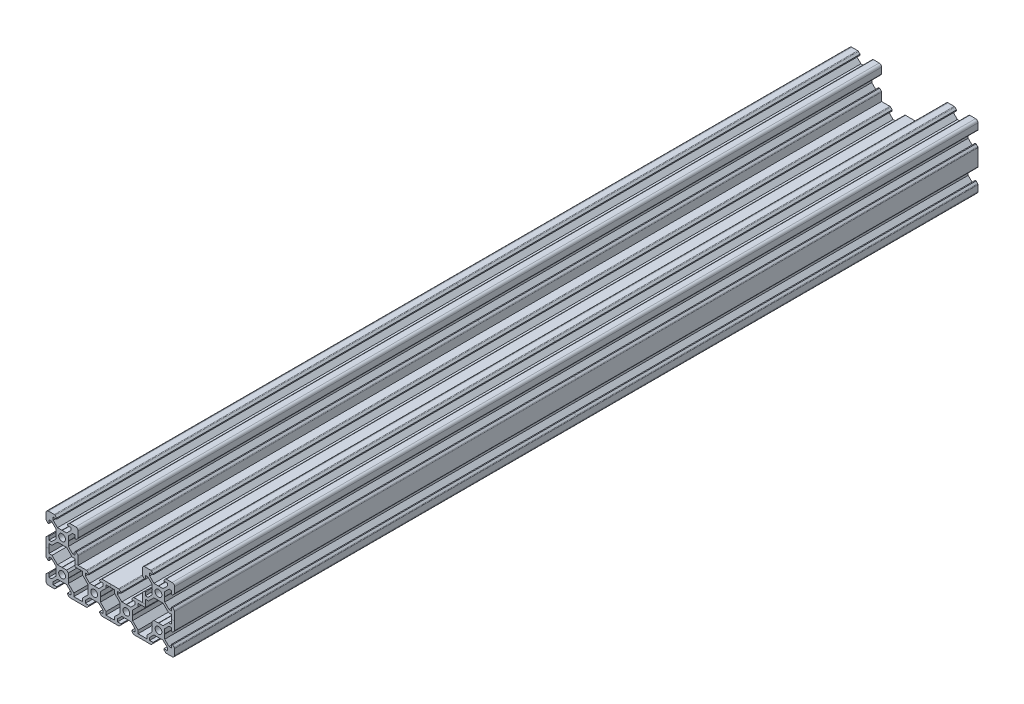
SolidWorks part; units mm, degrees
material "6063-T5"
ref_plane "Front" through (0, 0, 0) normal (0, 0, 1) x (1, 0, 0)
ref_plane "Top" through (0, 0, 0) normal (0, 1, 0) x (1, 0, 0)
ref_plane "Right" through (0, 0, 0) normal (1, 0, 0) x (0, 0, -1)
sketch "Sketch1" plane through (0, 0, 0) normal (0, 0, 1) x (1, 0, 0)
  line L0 (0, 32.3219) -> (0, -50.1713) construction
  line L1 (-2.8395, 3.9) -> (-0.1, 3.9)
  line L2 (-3.9, 2.8395) -> (-3.9, 0.1)
  line L3 (-2.8395, -3.9) -> (-0.1, -3.9)
  line L4 (3.9, 2.8395) -> (3.9, 0.1)
  line L5 (-29.7903, 0) -> (30, 0) construction
  line L6 (-0.1, -3.9) -> (0, -3.8)
  line L7 (-8.5, 10) -> (-4.8658, 10)
  line L8 (-10, 8.5) -> (-10, 4.8627)
  line L9 (-2.8395, -16.1) -> (-6.24, -12.6995)
  line L10 (10, 8.5) -> (10, 4.8627)
  line L11 (0, -3.8) -> (0.1, -3.9)
  line L12 (0.1, -3.9) -> (2.8395, -3.9)
  line L13 (-0.1, 3.9) -> (0, 3.8)
  line L14 (0, 3.8) -> (0.1, 3.9)
  line L15 (10, -10) -> (-10, 10) construction
  line L16 (-10, -10) -> (10, 10) construction
  line L17 (0.1, 3.9) -> (2.8395, 3.9)
  line L18 (-3.9, 0.1) -> (-3.8, 0)
  line L19 (-3.8, 0) -> (-3.9, -0.1)
  line L20 (-3.9, -0.1) -> (-3.9, -2.8395)
  line L21 (3.9, 0.1) -> (3.8, 0)
  line L22 (3.8, 0) -> (3.9, -0.1)
  line L23 (3.9, -0.1) -> (3.9, -2.8395)
  line L24 (0, -20) -> (58.4732, -20) construction
  line L25 (-3.9, 2.8395) -> (-6.561, 5.5005)
  line L26 (30, -50.1713) -> (30, 32.3219) construction
  line L27 (-5.5005, 8.2) -> (-3.3865, 8.2)
  line L28 (-8.2, 5.5005) -> (-8.2, 3.3865)
  line L29 (-10, -10) -> (-53.8942, -10) construction
  line L30 (8.2, 5.5005) -> (8.2, 3.3865)
  line L31 (-6.561, 5.5005) -> (-8.2, 5.5005)
  line L32 (-2.8395, 3.9) -> (-5.5005, 6.561)
  line L33 (-5.5005, 6.561) -> (-5.5005, 8.2)
  line L34 (6.561, 5.5005) -> (8.2, 5.5005)
  line L35 (3.9, 2.8395) -> (6.561, 5.5005)
  line L36 (5.5005, 6.561) -> (5.5005, 8.2)
  line L37 (2.8395, 3.9) -> (5.5005, 6.561)
  line L38 (6.561, -5.5005) -> (8.2, -5.5005)
  line L39 (-8.2, -12.6995) -> (-8.2, -7.3005)
  line L40 (2.8395, -3.9) -> (5.5005, -6.561)
  line L41 (3.9, -2.8395) -> (6.561, -5.5005)
  line L42 (-6.24, -12.6995) -> (-8.2, -12.6995)
  line L43 (-2.8395, -3.9) -> (-5.5005, -6.561)
  line L44 (-6.561, -5.5005) -> (-8.2, -5.5005)
  line L45 (-3.9, -2.8395) -> (-6.561, -5.5005)
  line L46 (30, -10) -> (10, -10) construction
  line L47 (-8.5, 10) -> (-10, 8.5) construction
  line L48 (8.5, 10) -> (10, 8.5) construction
  line L49 (-10, -10) -> (10, -30) construction
  line L50 (-5.5005, -6.561) -> (-6.24, -7.3005)
  line L51 (-3.9, -19.9) -> (-3.9, -17.1605)
  line L52 (-3.9, -17.1605) -> (-6.561, -14.4995)
  line L53 (10, 32.3219) -> (10, -50.1713) construction
  line L54 (-10, -30) -> (10, -10) construction
  line L55 (-4.3771, 9.7976) -> (-3.3865, 8.807)
  line L56 (-3.3865, 8.807) -> (-3.3865, 8.2)
  line L57 (4.3771, 9.7976) -> (3.3865, 8.807)
  line L58 (3.3865, 8.807) -> (3.3865, 8.2)
  line L59 (4.8658, 10) -> (8.5, 10)
  line L60 (3.3865, 8.2) -> (5.5005, 8.2)
  line L61 (-9.7968, 4.3732) -> (-8.807, 3.3865)
  line L62 (-8.807, 3.3865) -> (-8.2, 3.3865)
  line L63 (-9.7976, -4.3802) -> (-8.807, -3.3865)
  line L64 (-8.807, -3.3865) -> (-8.2, -3.3865)
  line L65 (9.7968, 4.3732) -> (8.807, 3.3865)
  line L66 (8.807, 3.3865) -> (8.2, 3.3865)
  line L67 (8.807, -3.3865) -> (8.2, -3.3865)
  line L68 (9.7976, -4.3802) -> (8.807, -3.3865)
  line L69 (-10, -4.87) -> (-10, -15.13)
  line L70 (-8.2, -3.3865) -> (-8.2, -5.5005)
  line L71 (10, -4.87) -> (10, -10)
  line L72 (8.2, -3.3865) -> (8.2, -5.5005)
  line L73 (-6.561, -14.4995) -> (-8.2, -14.4995)
  line L74 (-8.2, -16.6135) -> (-8.2, -14.4995)
  line L75 (-8.807, -16.6135) -> (-8.2, -16.6135)
  line L76 (-9.7976, -15.6198) -> (-8.807, -16.6135)
  line L77 (-10, -28.5) -> (-10, -24.8627)
  line L78 (-9.7968, -24.3732) -> (-8.807, -23.3865)
  line L79 (-8.807, -23.3865) -> (-8.2, -23.3865)
  line L80 (-8.2, -25.5005) -> (-8.2, -23.3865)
  line L81 (-6.561, -25.5005) -> (-8.2, -25.5005)
  line L82 (-3.9, -22.8395) -> (-6.561, -25.5005)
  line L83 (-3.9, -22.8395) -> (-3.9, -20.1)
  line L84 (-3.9, -20.1) -> (-3.8, -20)
  line L85 (-3.8, -20) -> (-3.9, -19.9)
  line L86 (0, -23.8) -> (0.1, -23.9)
  line L87 (-0.1, -23.9) -> (0, -23.8)
  line L88 (-2.8395, -23.9) -> (-0.1, -23.9)
  line L89 (0.1, -23.9) -> (2.8395, -23.9)
  line L90 (-2.8395, -23.9) -> (-5.5005, -26.561)
  line L91 (-5.5005, -28.2) -> (-3.3865, -28.2)
  line L92 (-5.5005, -26.561) -> (-5.5005, -28.2)
  line L93 (-4.3771, -29.7976) -> (-3.3865, -28.807)
  line L94 (-3.3865, -28.807) -> (-3.3865, -28.2)
  line L95 (-4.8658, -30) -> (-8.5, -30)
  line L96 (5.5005, -26.561) -> (5.5005, -28.2)
  line L97 (2.8395, -23.9) -> (5.5005, -26.561)
  line L98 (4.3771, -29.7976) -> (3.3865, -28.807)
  line L99 (3.3865, -28.807) -> (3.3865, -28.2)
  line L100 (3.3865, -28.2) -> (5.5005, -28.2)
  line L101 (4.8658, -30) -> (10, -30)
  line L102 (0.1, -16.1) -> (2.8395, -16.1)
  line L103 (0, -16.2) -> (0.1, -16.1)
  line L104 (-0.1, -16.1) -> (0, -16.2)
  line L105 (-2.8395, -16.1) -> (-0.1, -16.1)
  line L106 (3.9, -22.8395) -> (3.9, -20.1)
  line L107 (3.9, -20.1) -> (3.8, -20)
  line L108 (3.8, -20) -> (3.9, -19.9)
  line L109 (3.9, -19.9) -> (3.9, -17.1605)
  line L110 (3.9, -17.1605) -> (2.8395, -16.1)
  line L111 (-6.24, -7.3005) -> (-8.2, -7.3005)
  line L112 (6.24, -7.3005) -> (8.2, -7.3005)
  line L113 (5.5005, -6.561) -> (6.24, -7.3005)
  line L114 (12.6995, -28.2) -> (7.3005, -28.2)
  line L115 (7.3005, -28.2) -> (7.3005, -26.24)
  line L116 (7.3005, -26.24) -> (3.9, -22.8395)
  line L117 (16.1, -19.9) -> (16.1, -17.1605)
  line L118 (16.2, -20) -> (16.1, -19.9)
  line L119 (16.1, -20.1) -> (16.2, -20)
  line L120 (16.1, -22.8395) -> (16.1, -20.1)
  line L121 (20, -16.2) -> (19.9, -16.1)
  line L122 (20.1, -16.1) -> (20, -16.2)
  line L123 (22.8395, -16.1) -> (20.1, -16.1)
  line L124 (19.9, -16.1) -> (17.1605, -16.1)
  line L125 (23.9, -19.9) -> (23.9, -17.1605)
  line L126 (23.8, -20) -> (23.9, -19.9)
  line L127 (23.9, -20.1) -> (23.8, -20)
  line L128 (23.9, -22.8395) -> (23.9, -20.1)
  line L129 (20.1, -23.9) -> (20, -23.8)
  line L130 (22.8395, -23.9) -> (20.1, -23.9)
  line L131 (20, -23.8) -> (19.9, -23.9)
  line L132 (19.9, -23.9) -> (17.1605, -23.9)
  line L133 (12.6995, -28.2) -> (12.6995, -26.24)
  line L134 (14.4995, -26.561) -> (14.4995, -28.2)
  line L135 (17.1605, -23.9) -> (14.4995, -26.561)
  line L136 (12.6995, -26.24) -> (16.1, -22.8395)
  line L137 (16.6135, -28.807) -> (16.6135, -28.2)
  line L138 (16.6135, -28.2) -> (14.4995, -28.2)
  line L139 (15.6229, -29.7976) -> (16.6135, -28.807)
  line L140 (15.1342, -30) -> (10, -30)
  line L141 (20, 32.3219) -> (20, -50.1713) construction
  line L142 (10, -10) -> (30, -30) construction
  line L143 (30, -10) -> (10, -30) construction
  line L144 (27.3005, -28.2) -> (27.3005, -26.24)
  line L145 (25.5005, -26.561) -> (25.5005, -28.2)
  line L146 (24.3771, -29.7976) -> (23.3865, -28.807)
  line L147 (23.3865, -28.807) -> (23.3865, -28.2)
  line L148 (23.3865, -28.2) -> (25.5005, -28.2)
  line L149 (24.8658, -30) -> (30, -30)
  line L150 (27.3005, -28.2) -> (32.6995, -28.2)
  line L151 (25.5005, -26.561) -> (22.8395, -23.9)
  line L152 (27.3005, -26.24) -> (23.9, -22.8395)
  line L153 (25.5005, -13.439) -> (25.5005, -11.8)
  line L154 (27.3005, -11.8) -> (27.3005, -13.76)
  line L155 (27.3005, -13.76) -> (23.9, -17.1605)
  line L156 (25.5005, -13.439) -> (22.8395, -16.1)
  line L157 (12.6995, -11.8) -> (12.6995, -13.76)
  line L158 (14.4995, -13.439) -> (14.4995, -11.8)
  line L159 (17.1605, -16.1) -> (14.4995, -13.439)
  line L160 (16.1, -17.1605) -> (12.6995, -13.76)
  line L161 (23.3865, -11.193) -> (23.3865, -11.8)
  line L162 (16.6135, -11.193) -> (16.6135, -11.8)
  line L163 (16.6135, -11.8) -> (14.4995, -11.8)
  line L164 (23.3865, -11.8) -> (25.5005, -11.8)
  line L165 (15.6229, -10.2024) -> (16.6135, -11.193)
  line L166 (24.3771, -10.2024) -> (23.3865, -11.193)
  line L167 (24.8658, -10) -> (30, -10)
  line L168 (27.3005, -11.8) -> (32.6995, -11.8)
  line L169 (15.1342, -10) -> (10, -10)
  line L170 (12.6995, -11.8) -> (8.2, -11.8)
  line L171 (8.2, -11.8) -> (8.2, -7.3005)
  line L172 (60, -3.8) -> (59.9, -3.9)
  line L173 (60.1, -3.9) -> (60, -3.8)
  line L174 (63.8, 0) -> (63.9, -0.1)
  line L175 (63.9, 0.1) -> (63.8, 0)
  line L176 (56.1, 0.1) -> (56.2, 0)
  line L177 (56.2, 0) -> (56.1, -0.1)
  line L178 (60.1, 3.9) -> (60, 3.8)
  line L179 (60, 3.8) -> (59.9, 3.9)
  line L180 (62.8395, 3.9) -> (60.1, 3.9)
  line L181 (59.9, 3.9) -> (57.1605, 3.9)
  line L182 (63.9, 2.8395) -> (63.9, 0.1)
  line L183 (63.9, -0.1) -> (63.9, -2.8395)
  line L184 (62.8395, -3.9) -> (60.1, -3.9)
  line L185 (59.9, -3.9) -> (57.1605, -3.9)
  line L186 (56.1, -0.1) -> (56.1, -2.8395)
  line L187 (56.1, 2.8395) -> (56.1, 0.1)
  line L188 (60, -23.8) -> (59.9, -23.9)
  line L189 (60.1, -23.9) -> (60, -23.8)
  line L190 (60, -16.2) -> (59.9, -16.1)
  line L191 (60.1, -16.1) -> (60, -16.2)
  line L192 (63.8, -20) -> (63.9, -19.9)
  line L193 (63.9, -20.1) -> (63.8, -20)
  line L194 (56.2, -20) -> (56.1, -19.9)
  line L195 (56.1, -20.1) -> (56.2, -20)
  line L196 (40, -16.2) -> (40.1, -16.1)
  line L197 (39.9, -16.1) -> (40, -16.2)
  line L198 (36.2, -20) -> (36.1, -19.9)
  line L199 (36.1, -20.1) -> (36.2, -20)
  line L200 (43.8, -20) -> (43.9, -19.9)
  line L201 (43.9, -20.1) -> (43.8, -20)
  line L202 (40, -23.8) -> (40.1, -23.9)
  line L203 (39.9, -23.9) -> (40, -23.8)
  line L204 (56.1, -22.8395) -> (56.1, -20.1)
  line L205 (59.9, -23.9) -> (57.1605, -23.9)
  line L206 (62.8395, -23.9) -> (60.1, -23.9)
  line L207 (63.9, -22.8395) -> (63.9, -20.1)
  line L208 (63.9, -19.9) -> (63.9, -17.1605)
  line L209 (62.8395, -16.1) -> (60.1, -16.1)
  line L210 (59.9, -16.1) -> (57.1605, -16.1)
  line L211 (56.1, -19.9) -> (56.1, -17.1605)
  line L212 (43.9, -19.9) -> (43.9, -17.1605)
  line L213 (43.9, -22.8395) -> (43.9, -20.1)
  line L214 (40.1, -23.9) -> (42.8395, -23.9)
  line L215 (37.1605, -23.9) -> (39.9, -23.9)
  line L216 (36.1, -22.8395) -> (36.1, -20.1)
  line L217 (36.1, -19.9) -> (36.1, -17.1605)
  line L218 (37.1605, -16.1) -> (39.9, -16.1)
  line L219 (40.1, -16.1) -> (42.8395, -16.1)
  line L220 (42.8395, -23.9) -> (45.5005, -26.561)
  line L221 (47.3005, -26.24) -> (43.9, -22.8395)
  line L222 (43.9, -17.1605) -> (47.3005, -13.76)
  line L223 (42.8395, -16.1) -> (45.5005, -13.439)
  line L224 (34.4995, -13.439) -> (37.1605, -16.1)
  line L225 (32.6995, -13.76) -> (36.1, -17.1605)
  line L226 (34.4995, -26.561) -> (37.1605, -23.9)
  line L227 (32.6995, -26.24) -> (36.1, -22.8395)
  line L228 (47.3005, -11.8) -> (47.3005, -13.76)
  line L229 (45.5005, -13.439) -> (45.5005, -11.8)
  line L230 (47.3005, -28.2) -> (47.3005, -26.24)
  line L231 (45.5005, -26.561) -> (45.5005, -28.2)
  line L232 (34.4995, -26.561) -> (34.4995, -28.2)
  line L233 (32.6995, -28.2) -> (32.6995, -26.24)
  line L234 (34.4995, -13.439) -> (34.4995, -11.8)
  line L235 (32.6995, -11.8) -> (32.6995, -13.76)
  line L236 (43.3865, -28.2) -> (45.5005, -28.2)
  line L237 (43.3865, -28.807) -> (43.3865, -28.2)
  line L238 (44.3771, -29.7976) -> (43.3865, -28.807)
  line L239 (35.6229, -29.7976) -> (36.6135, -28.807)
  line L240 (36.6135, -28.807) -> (36.6135, -28.2)
  line L241 (36.6135, -28.2) -> (34.4995, -28.2)
  line L242 (44.3771, -10.2024) -> (43.3865, -11.193)
  line L243 (43.3865, -11.193) -> (43.3865, -11.8)
  line L244 (43.3865, -11.8) -> (45.5005, -11.8)
  line L245 (35.6229, -10.2024) -> (36.6135, -11.193)
  line L246 (36.6135, -11.193) -> (36.6135, -11.8)
  line L247 (36.6135, -11.8) -> (34.4995, -11.8)
  line L248 (35.1342, -30) -> (30, -30)
  line L249 (35.1342, -10) -> (30, -10)
  line L250 (51.8, -3.3865) -> (51.8, -5.5005)
  line L251 (51.193, -3.3865) -> (51.8, -3.3865)
  line L252 (50.2024, -4.3802) -> (51.193, -3.3865)
  line L253 (51.8, -11.8) -> (51.8, -7.3005)
  line L254 (50, -4.87) -> (50, -10)
  line L255 (44.8658, -10) -> (50, -10)
  line L256 (47.3005, -11.8) -> (51.8, -11.8)
  line L257 (62.8395, -16.1) -> (66.24, -12.6995)
  line L258 (63.9, -17.1605) -> (66.561, -14.4995)
  line L259 (63.9, -22.8395) -> (66.561, -25.5005)
  line L260 (62.8395, -23.9) -> (65.5005, -26.561)
  line L261 (57.1605, -23.9) -> (54.4995, -26.561)
  line L262 (52.6995, -26.24) -> (56.1, -22.8395)
  line L263 (63.9, 2.8395) -> (66.561, 5.5005)
  line L264 (62.8395, 3.9) -> (65.5005, 6.561)
  line L265 (57.1605, 3.9) -> (54.4995, 6.561)
  line L266 (56.1, 2.8395) -> (53.439, 5.5005)
  line L267 (63.9, -2.8395) -> (66.561, -5.5005)
  line L268 (62.8395, -3.9) -> (65.5005, -6.561)
  line L269 (57.1605, -3.9) -> (54.4995, -6.561)
  line L270 (56.1, -2.8395) -> (53.439, -5.5005)
  line L271 (64.3771, -29.7976) -> (63.3865, -28.807)
  line L272 (64.8658, -30) -> (68.5, -30)
  line L273 (65.5005, -28.2) -> (63.3865, -28.2)
  line L274 (55.6229, -29.7976) -> (56.6135, -28.807)
  line L275 (56.6135, -28.2) -> (54.4995, -28.2)
  line L276 (56.6135, -28.807) -> (56.6135, -28.2)
  line L277 (55.1342, -30) -> (50, -30)
  line L278 (44.8658, -30) -> (50, -30)
  line L279 (44.3771, -29.7976) -> (43.3865, -28.807)
  line L280 (43.3865, -28.807) -> (43.3865, -28.2)
  line L281 (43.3865, -28.2) -> (45.5005, -28.2)
  line L282 (47.3005, -28.2) -> (52.6995, -28.2)
  line L283 (70, -28.5) -> (70, -24.8627)
  line L284 (65.5005, -26.561) -> (65.5005, -28.2)
  line L285 (54.4995, -26.561) -> (54.4995, -28.2)
  line L286 (52.6995, -28.2) -> (52.6995, -26.24)
  line L287 (47.3005, -28.2) -> (47.3005, -26.24)
  line L288 (45.5005, -26.561) -> (45.5005, -28.2)
  line L289 (66.561, -5.5005) -> (68.2, -5.5005)
  line L290 (66.24, -7.3005) -> (68.2, -7.3005)
  line L291 (69.7976, -4.3802) -> (68.807, -3.3865)
  line L292 (68.807, -3.3865) -> (68.2, -3.3865)
  line L293 (68.2, -3.3865) -> (68.2, -5.5005)
  line L294 (68.2, -12.6995) -> (68.2, -7.3005)
  line L295 (70, -4.87) -> (70, -15.13)
  line L296 (69.7976, -15.6198) -> (68.807, -16.6135)
  line L297 (68.807, -16.6135) -> (68.2, -16.6135)
  line L298 (68.2, -16.6135) -> (68.2, -14.4995)
  line L299 (66.561, -14.4995) -> (68.2, -14.4995)
  line L300 (66.24, -12.6995) -> (68.2, -12.6995)
  line L301 (56.1, -17.1605) -> (57.1605, -16.1)
  line L302 (66.561, -25.5005) -> (68.2, -25.5005)
  line L303 (68.2, -25.5005) -> (68.2, -23.3865)
  line L304 (68.807, -23.3865) -> (68.2, -23.3865)
  line L305 (69.7968, -24.3732) -> (68.807, -23.3865)
  line L306 (53.76, -7.3005) -> (51.8, -7.3005)
  line L307 (53.439, -5.5005) -> (51.8, -5.5005)
  line L308 (54.4995, -6.561) -> (53.76, -7.3005)
  line L309 (65.5005, -6.561) -> (66.24, -7.3005)
  line L310 (54.4995, 6.561) -> (54.4995, 8.2)
  line L311 (56.6135, 8.2) -> (54.4995, 8.2)
  line L312 (56.6135, 8.807) -> (56.6135, 8.2)
  line L313 (55.6229, 9.7976) -> (56.6135, 8.807)
  line L314 (55.1342, 10) -> (51.5, 10)
  line L315 (50, 8.5) -> (50, 4.8627)
  line L316 (50.2032, 4.3732) -> (51.193, 3.3865)
  line L317 (51.193, 3.3865) -> (51.8, 3.3865)
  line L318 (51.8, 5.5005) -> (51.8, 3.3865)
  line L319 (53.439, 5.5005) -> (51.8, 5.5005)
  line L320 (66.561, 5.5005) -> (68.2, 5.5005)
  line L321 (68.2, 5.5005) -> (68.2, 3.3865)
  line L322 (68.807, 3.3865) -> (68.2, 3.3865)
  line L323 (69.7968, 4.3732) -> (68.807, 3.3865)
  line L324 (70, 8.5) -> (70, 4.8627)
  line L325 (68.5, 10) -> (64.8658, 10)
  line L326 (64.3771, 9.7976) -> (63.3865, 8.807)
  line L327 (63.3865, 8.807) -> (63.3865, 8.2)
  line L328 (65.5005, 8.2) -> (63.3865, 8.2)
  line L329 (65.5005, 6.561) -> (65.5005, 8.2)
  line L330 (63.3865, -28.807) -> (63.3865, -28.2)
  circle A0 centre (0, 0) radius 2.1
  circle A1 centre (0, -20) radius 2.1
  circle A2 centre (20, -20) radius 2.1
  circle A3 centre (60, 0) radius 2.1
  circle A4 centre (60, -20) radius 2.1
  circle A5 centre (40, -20) radius 2.1
  arc A6 (-8.5, 10) -> (-10, 8.5) centre (-8.5, 8.5) ccw
  arc A7 (10, 8.5) -> (8.5, 10) centre (8.5, 8.5) ccw
  arc A8 (-4.3771, 9.7976) -> (-4.8658, 10) centre (-4.8658, 9.3088) ccw
  arc A9 (4.3771, 9.7976) -> (4.8658, 10) centre (4.8658, 9.3088) cw
  arc A10 (-10, 4.8627) -> (-9.7968, 4.3732) centre (-9.3088, 4.8627) ccw
  arc A11 (9.7968, 4.3732) -> (10, 4.8627) centre (9.3088, 4.8627) ccw
  arc A12 (10, -4.87) -> (9.7976, -4.3802) centre (9.3062, -4.87) ccw
  arc A13 (-9.7976, -4.3802) -> (-10, -4.87) centre (-9.3062, -4.87) ccw
  arc A14 (-9.7976, -15.6198) -> (-10, -15.13) centre (-9.3062, -15.13) cw
  arc A15 (-8.5, -30) -> (-10, -28.5) centre (-8.5, -28.5) cw
  arc A16 (-10, -24.8627) -> (-9.7968, -24.3732) centre (-9.3088, -24.8627) cw
  arc A17 (-4.3771, -29.7976) -> (-4.8658, -30) centre (-4.8658, -29.3088) cw
  arc A18 (4.3771, -29.7976) -> (4.8658, -30) centre (4.8658, -29.3088) ccw
  arc A19 (15.6229, -29.7976) -> (15.1342, -30) centre (15.1342, -29.3088) cw
  arc A20 (24.3771, -29.7976) -> (24.8658, -30) centre (24.8658, -29.3088) ccw
  arc A21 (15.6229, -10.2024) -> (15.1342, -10) centre (15.1342, -10.6912) ccw
  arc A22 (24.3771, -10.2024) -> (24.8658, -10) centre (24.8658, -10.6912) cw
  arc A23 (44.3771, -29.7976) -> (44.8658, -30) centre (44.8658, -29.3088) ccw
  arc A24 (35.6229, -29.7976) -> (35.1342, -30) centre (35.1342, -29.3088) cw
  arc A25 (44.3771, -10.2024) -> (44.8658, -10) centre (44.8658, -10.6912) cw
  arc A26 (35.6229, -10.2024) -> (35.1342, -10) centre (35.1342, -10.6912) ccw
  arc A27 (50, -4.87) -> (50.2024, -4.3802) centre (50.6938, -4.87) cw
  arc A28 (64.3771, -29.7976) -> (64.8658, -30) centre (64.8658, -29.3088) ccw
  arc A29 (68.5, -30) -> (70, -28.5) centre (68.5, -28.5) ccw
  arc A30 (55.6229, -29.7976) -> (55.1342, -30) centre (55.1342, -29.3088) cw
  arc A31 (44.3771, -29.7976) -> (44.8658, -30) centre (44.8658, -29.3088) ccw
  arc A32 (69.7976, -4.3802) -> (70, -4.87) centre (69.3062, -4.87) cw
  arc A33 (69.7976, -15.6198) -> (70, -15.13) centre (69.3062, -15.13) ccw
  arc A34 (70, -24.8627) -> (69.7968, -24.3732) centre (69.3088, -24.8627) ccw
  arc A35 (55.6229, 9.7976) -> (55.1342, 10) centre (55.1342, 9.3088) ccw
  arc A36 (50, 8.5) -> (51.5, 10) centre (51.5, 8.5) cw
  arc A37 (50.2032, 4.3732) -> (50, 4.8627) centre (50.6912, 4.8627) cw
  arc A38 (70, 4.8627) -> (69.7968, 4.3732) centre (69.3088, 4.8627) cw
  arc A39 (68.5, 10) -> (70, 8.5) centre (68.5, 8.5) cw
  arc A40 (64.3771, 9.7976) -> (64.8658, 10) centre (64.8658, 9.3088) cw
  point P23 (-9.25, 9.25)
  point P69 (9.25, 9.25)
  point P188 (10, -28.2)
  point P223 (30, -28.2)
  point P320 (30, -11.8)
  dimension "D1" = 4.2
  dimension "D16" = 1.5
  dimension "D21" = 0.529
  dimension "D25" = 0.53
  dimension "D27" = 90
  dimension "D2" = 0.1
  dimension "D3" = 0.1
  dimension "D4" = 7.8
  dimension "D5" = 7.8
  dimension "D6" = 20
  dimension "D7" = 20
  dimension "D8" = 20
  dimension "D9" = 10
  dimension "D10" = 0.1
  dimension "D11" = 1.8
  dimension "D12" = 1.8
  dimension "D13" = 5.679
  dimension "D14" = 5.679
  dimension "D15" = 1.639
  dimension "D17" = 90
  dimension "D18" = 6.773
  dimension "D19" = 0.607
  dimension "D20" = 11.001
  dimension "D22" = 0.607
  dimension "D23" = 90
  dimension "D24" = 6.773
  dimension "D26" = 0.53
  dimension "D28" = 0.53
  dimension "D29" = 0.53
  dimension "D30" = 1.8
extrude "Boss-Extrude1" add sketch "Sketch1" along normal blind 500 contours A40 L326 L327 L328 L329 L264 L180 L178 L179 L181 L265 L310 L311 L312 L313 A35 L314 A36 L315 A37 L316 L317 L318 L319 L266 L187 L176 L177 L186 L270 L307 L250 L251 L252 A27 L254 L255 A25 L242 L243 L244 L229 L223 L219 L196 L197 L218 L224 L234 L247 L246
sketch "Sketch2" plane through (0, 0, 500) normal (0, 0, 1) x (1, 0, 0)
  line L0 (-10, -10) -> (70, -10)
  line L1 (-10, -4.87) -> (-10, -15.13) construction
  line L2 (70, -4.87) -> (70, -15.13) construction
split line "TopFixture1 - SplitLine"
sketch "Sketch3" plane through (0, 0, 0) normal (0, 0, -1) x (-1, 0, 0)
  line L0 (-70, -10) -> (10, -10)
  line L1 (-70, -4.87) -> (-70, -15.13) construction
  line L2 (10, -4.87) -> (10, -15.13) construction
split line "TopFixture2 - SplitLine"
sketch "Sketch6" plane through (0, 10, 0) normal (0, 1, 0) x (1, 0, 0)
  line L0 (-8.5, -250) -> (68.5, -250)
  line L1 (-8.5, -500) -> (-8.5, 0) construction
  line L2 (68.5, -500) -> (68.5, 0) construction
split line "TopFixture3 - SplitLine"
sketch "Sketch7" plane through (0, 0, 500) normal (0, 0, 1) x (1, 0, 0)
  line L0 (30, -30) -> (30, -10)
  line L1 (24.8658, -30) -> (35.1342, -30) construction
  line L2 (35.1342, -10) -> (24.8658, -10) construction
split line "SideFixture1 - SplitLine"
sketch "Sketch8" plane through (0, 0, 0) normal (0, 0, -1) x (-1, 0, 0)
  line L0 (-30, -10) -> (-30, -30)
  line L1 (-35.1342, -10) -> (-24.8658, -10) construction
  line L2 (-24.8658, -30) -> (-35.1342, -30) construction
split line "SideFixture2 - SplitLine"
sketch "Sketch9" plane through (-10, 0, 0) normal (-1, 0, 0) x (0, 0, 1)
  line L0 (250, -28.5) -> (250, 8.5)
  line L3 (500, -28.5) -> (0, -28.5) construction
  line L4 (500, 8.5) -> (0, 8.5) construction
split line "SideFixture3 - SplitLine"
equation "\"base-xwidth\"= 500mm"
equation "\"base-yheight\"= 500mm"
equation "\"base-zdepth\" = 500mm"
equation "\"D1@Boss-Extrude1\"=\"base-zdepth\""
